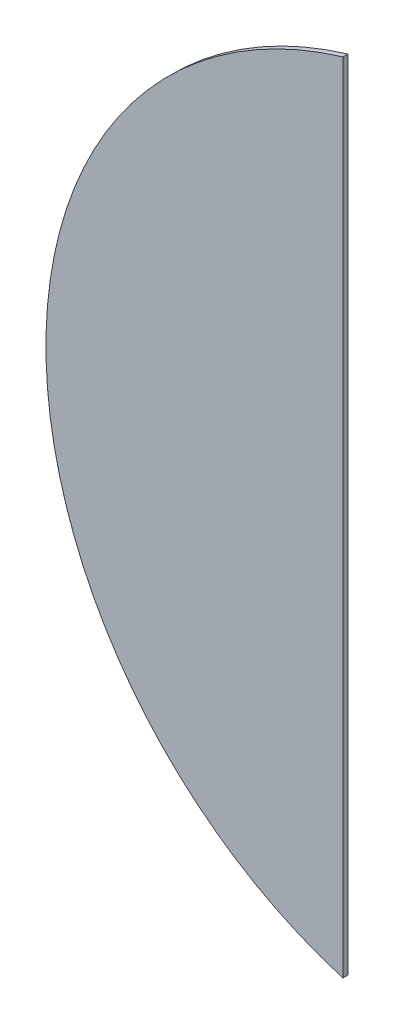
SolidWorks part; units mm, degrees
ref_plane "Front Plane" through (0, 0, 0) normal (0, 0, 1) x (1, 0, 0)
ref_plane "Top Plane" through (0, 0, 0) normal (0, 1, 0) x (1, 0, 0)
ref_plane "Right Plane" through (0, 0, 0) normal (1, 0, 0) x (0, 0, -1)
sketch "Sketch1" plane through (0, 0, 0) normal (0, 0, 1) x (1, 0, 0)
  line L0 (439.4644, 159.7589) -> (439.4644, -159.7589)
  arc A0 (439.4644, 159.7589) -> (439.4644, -159.7589) centre (487.2745, 0) ccw
  point P4 (0, 0)
extrude "Boss-Extrude1" add sketch "Sketch1" along normal blind 2
